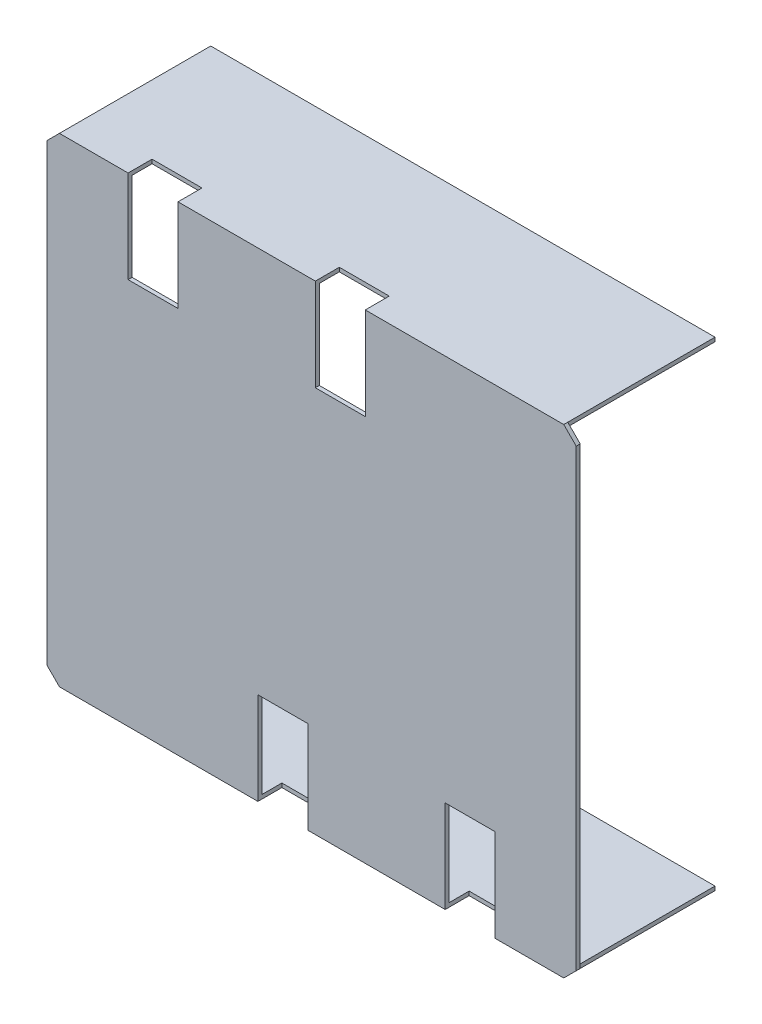
SolidWorks part; units mm, degrees
ref_plane "Front Plane" through (0, 0, 0) normal (0, 0, 1) x (1, 0, 0)
ref_plane "Top Plane" through (0, 0, 0) normal (0, 1, 0) x (1, 0, 0)
ref_plane "Right Plane" through (0, 0, 0) normal (1, 0, 0) x (0, 0, -1)
sketch "Sketch1" plane through (0, 0, 0) normal (0, 0, 1) x (1, 0, 0)
  line L0 (-101, -96) -> (101, -96)
  line L1 (101, -96) -> (106, -91)
  line L2 (106, -91) -> (106, 91)
  line L3 (106, 91) -> (101, 96)
  line L4 (101, 96) -> (-101, 96)
  line L5 (-101, 96) -> (-106, 91)
  line L6 (-106, 91) -> (-106, -91)
  line L7 (-106, -91) -> (-101, -96)
extrude "5052 sheet top panel" add sketch "Sketch1" along normal blind 1.6 from offset 86
sketch "Sketch2" plane through (0, 0, 0) normal (0, 0, 1) x (1, 0, 0)
  line L0 (-101, 94.4) -> (101, 94.4)
  line L1 (101, 94.4) -> (101, 96)
  line L2 (101, 96) -> (-101, 96)
  line L3 (-101, 96) -> (-101, 94.4)
  line L4 (-101, -96) -> (101, -96)
  line L5 (101, -96) -> (101, -94.4)
  line L6 (101, -94.4) -> (-101, -94.4)
  line L7 (-101, -94.4) -> (-101, -96)
extrude "Folded side skirts with open ends" add sketch "Sketch2" along normal blind 59 from offset 27
sketch "Sketch3" plane through (0, 0, 0) normal (0, 0, 1) x (1, 0, 0)
  line L0 (-73.5, 59) -> (-53.5, 59)
  line L1 (-53.5, 59) -> (-53.5, 97)
  line L2 (-53.5, 97) -> (-73.5, 97)
  line L3 (-73.5, 97) -> (-73.5, 59)
  line L4 (53.5, -97) -> (73.5, -97)
  line L5 (73.5, -97) -> (73.5, -59)
  line L6 (73.5, -59) -> (53.5, -59)
  line L7 (53.5, -59) -> (53.5, -97)
  line L8 (1.5, 59) -> (21.5, 59)
  line L9 (21.5, 59) -> (21.5, 97)
  line L10 (21.5, 97) -> (1.5, 97)
  line L11 (1.5, 97) -> (1.5, 59)
  line L12 (-21.5, -97) -> (-1.5, -97)
  line L13 (-1.5, -97) -> (-1.5, -59)
  line L14 (-1.5, -59) -> (-21.5, -59)
  line L15 (-21.5, -59) -> (-21.5, -97)
extrude "Four side-open hose and wrench slots" cut sketch "Sketch3" along normal blind 9.6 from offset 78
